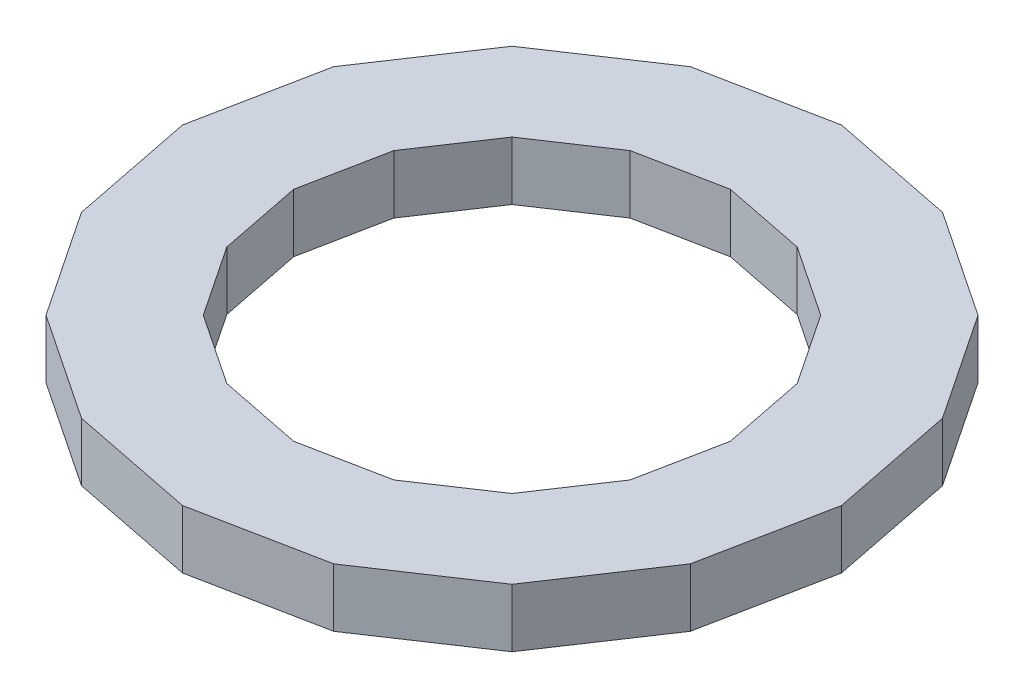
SolidWorks part; units mm, degrees
ref_plane "Front Plane" through (0, 0, 0) normal (0, 0, 1) x (1, 0, 0)
ref_plane "Top Plane" through (0, 0, 0) normal (0, 1, 0) x (1, 0, 0)
ref_plane "Right Plane" through (0, 0, 0) normal (1, 0, 0) x (0, 0, -1)
sketch "Sketch1" plane through (0, 0, 0) normal (0, 1, 0) x (1, 0, 0)
  line L1 (71.1551, 0) -> (65.7388, 27.2299)
  line L2 (65.7388, 27.2299) -> (50.3143, 50.3143)
  line L3 (50.3143, 50.3143) -> (27.2299, 65.7388)
  line L4 (27.2299, 65.7388) -> (0, 71.1551)
  line L5 (0, 71.1551) -> (-27.2299, 65.7388)
  line L6 (-27.2299, 65.7388) -> (-50.3143, 50.3143)
  line L7 (-50.3143, 50.3143) -> (-65.7388, 27.2299)
  line L8 (-65.7388, 27.2299) -> (-71.1551, 0)
  line L9 (-71.1551, 0) -> (-65.7388, -27.2299)
  line L10 (-65.7388, -27.2299) -> (-50.3143, -50.3143)
  line L11 (-50.3143, -50.3143) -> (-27.2299, -65.7388)
  line L12 (-27.2299, -65.7388) -> (0, -71.1551)
  line L13 (0, -71.1551) -> (27.2299, -65.7388)
  line L14 (27.2299, -65.7388) -> (50.3143, -50.3143)
  line L15 (50.3143, -50.3143) -> (65.7388, -27.2299)
  line L16 (65.7388, -27.2299) -> (71.1551, 0)
  line L17 (107.4118, 0) -> (99.2356, 41.1047)
  line L18 (99.2356, 41.1047) -> (75.9516, 75.9516)
  line L19 (75.9516, 75.9516) -> (41.1047, 99.2356)
  line L20 (41.1047, 99.2356) -> (0, 107.4118)
  line L21 (0, 107.4118) -> (-41.1047, 99.2356)
  line L22 (-41.1047, 99.2356) -> (-75.9516, 75.9516)
  line L23 (-75.9516, 75.9516) -> (-99.2356, 41.1047)
  line L24 (-99.2356, 41.1047) -> (-107.4118, 0)
  line L25 (-107.4118, 0) -> (-99.2356, -41.1047)
  line L26 (-99.2356, -41.1047) -> (-75.9516, -75.9516)
  line L27 (-75.9516, -75.9516) -> (-41.1047, -99.2356)
  line L28 (-41.1047, -99.2356) -> (0, -107.4118)
  line L29 (0, -107.4118) -> (41.1047, -99.2356)
  line L30 (41.1047, -99.2356) -> (75.9516, -75.9516)
  line L31 (75.9516, -75.9516) -> (99.2356, -41.1047)
  line L32 (99.2356, -41.1047) -> (107.4118, 0)
  circle A0 centre (0, 0) radius 69.7879 construction
  circle A1 centre (0, 0) radius 105.3479 construction
  dimension "D1" = 41.91
  dimension "D2" = 35.56
extrude "Boss-Extrude1" add sketch "Sketch1" along normal blind 19.05
